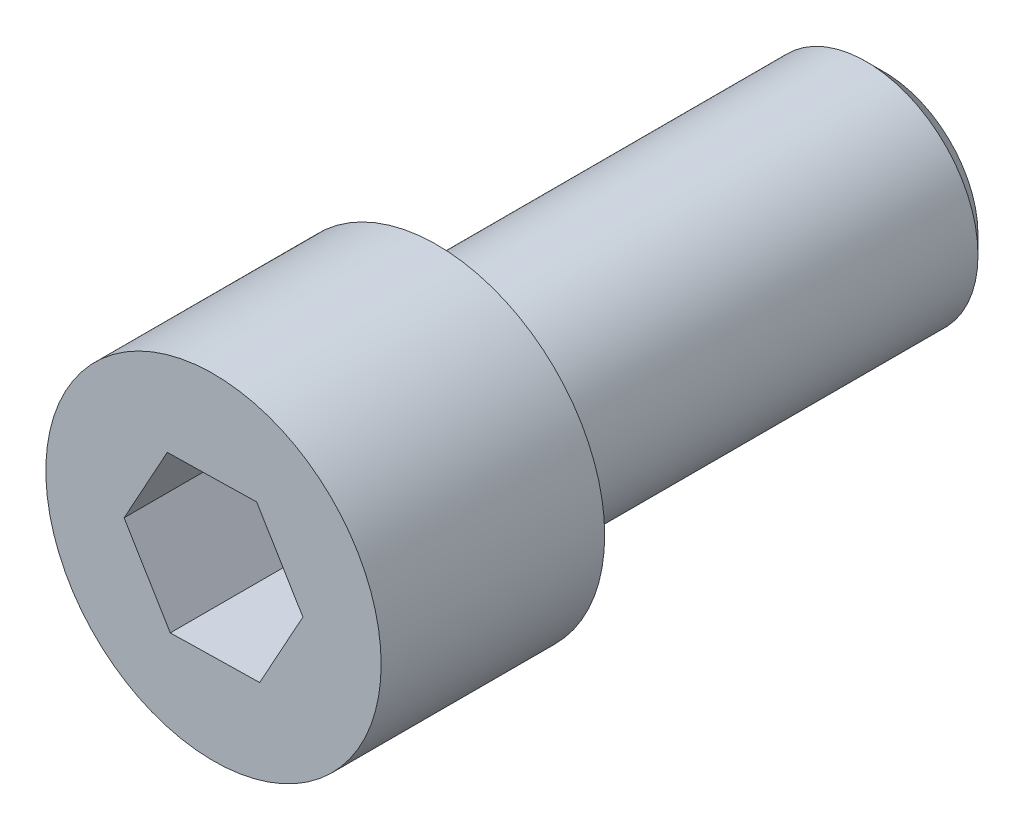
SolidWorks part; units mm, degrees
material "Plain Carbon Steel"
ref_plane "Front Plane" through (0, 0, 0) normal (0, 0, 1) x (1, 0, 0)
ref_plane "Top Plane" through (0, 0, 0) normal (0, 1, 0) x (1, 0, 0)
ref_plane "Right Plane" through (0, 0, 0) normal (1, 0, 0) x (0, 0, -1)
sketch "Sketch1" plane through (0, 0, 0) normal (0, 0, 1) x (1, 0, 0)
  circle A0 centre (-30.0924, 3.6145) radius 4.7625
  dimension "D1" = 9.525
extrude "Boss-Extrude1" add sketch "Sketch1" along normal blind 6.35
sketch "Sketch2" plane through (0, 0, 6.35) normal (0, 0, 1) x (1, 0, 0)
  line L1 (-28.7803, 1.4396) -> (-27.5529, 3.6634)
  line L2 (-27.5529, 3.6634) -> (-28.865, 5.8382)
  line L3 (-28.865, 5.8382) -> (-31.4046, 5.7893)
  line L4 (-31.4046, 5.7893) -> (-32.6319, 3.5655)
  line L5 (-32.6319, 3.5655) -> (-31.3198, 1.3907)
  line L6 (-31.3198, 1.3907) -> (-28.7803, 1.4396)
  circle A0 centre (-30.0924, 3.6145) radius 2.1997 construction
  dimension "D1" = 5.08
  dimension "D2" = 5.0791
extrude "Cut-Extrude1" cut sketch "Sketch2" against normal blind 3.81
sketch "Sketch3" plane through (0, 0, 0) normal (0, 0, -1) x (-1, 0, 0)
  circle A0 centre (30.0924, 3.6145) radius 3.175
  dimension "D1" = 6.35
extrude "Boss-Extrude2" add sketch "Sketch3" along normal blind 12.7
fillet "Fillet1" radius 0.381 1 edges at (-33.2674, 3.6145, 0)
chamfer "Chamfer1" distance 0.508 angle 45 1 edges at (-33.2674, 3.6145, -12.7)
